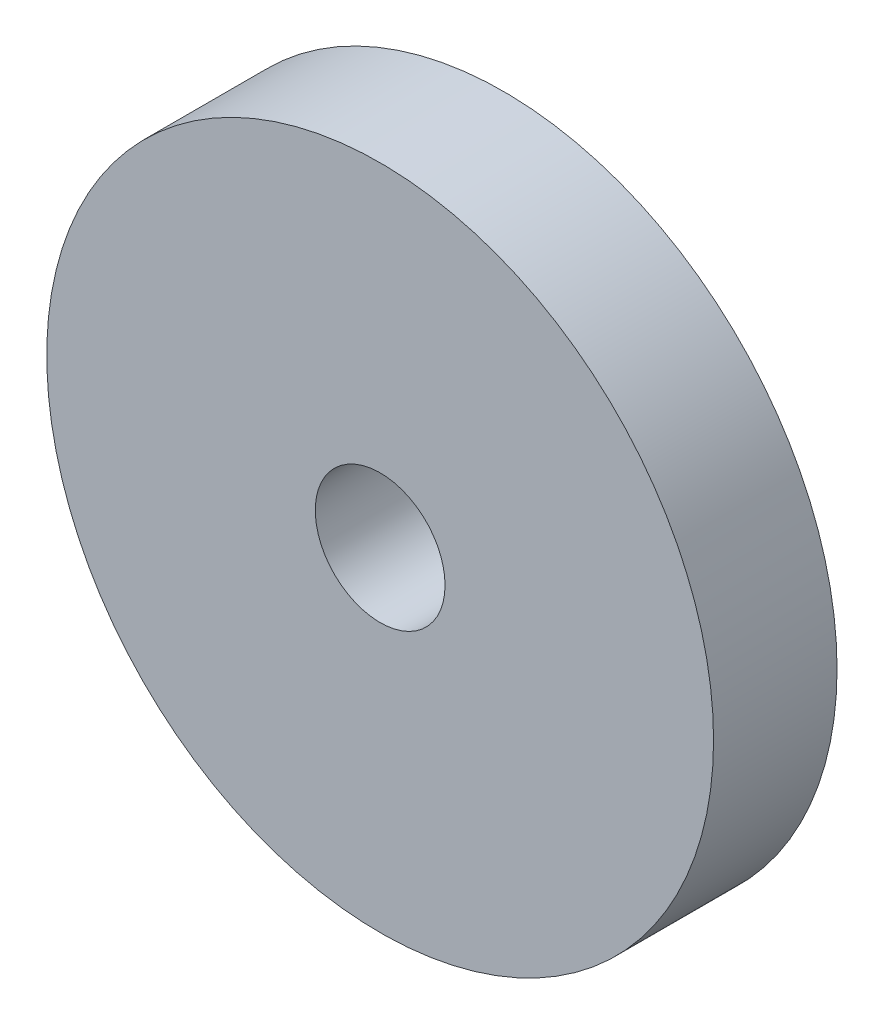
SolidWorks part; units mm, degrees
ref_plane "Front Plane" through (0, 0, 0) normal (0, 0, 1) x (1, 0, 0)
ref_plane "Top Plane" through (0, 0, 0) normal (0, 1, 0) x (1, 0, 0)
ref_plane "Right Plane" through (0, 0, 0) normal (1, 0, 0) x (0, 0, -1)
sketch "Sketch2" plane through (0, 0, 0) normal (0, 0, 1) x (1, 0, 0)
  circle A0 centre (0, 0) radius 13.5
  dimension "D1" = 27
extrude "Boss-Extrude1" add sketch "Sketch2" along normal blind 5
sketch "Sketch3" plane through (0, 0, 5) normal (0, 0, 1) x (1, 0, 0)
  circle A0 centre (0, 0) radius 2.627
  dimension "D1" = 5.254
extrude "Cut-Extrude1" cut sketch "Sketch3" against normal blind 5
equation "\"D1@Sketch3\"=5mm+0.01in"
